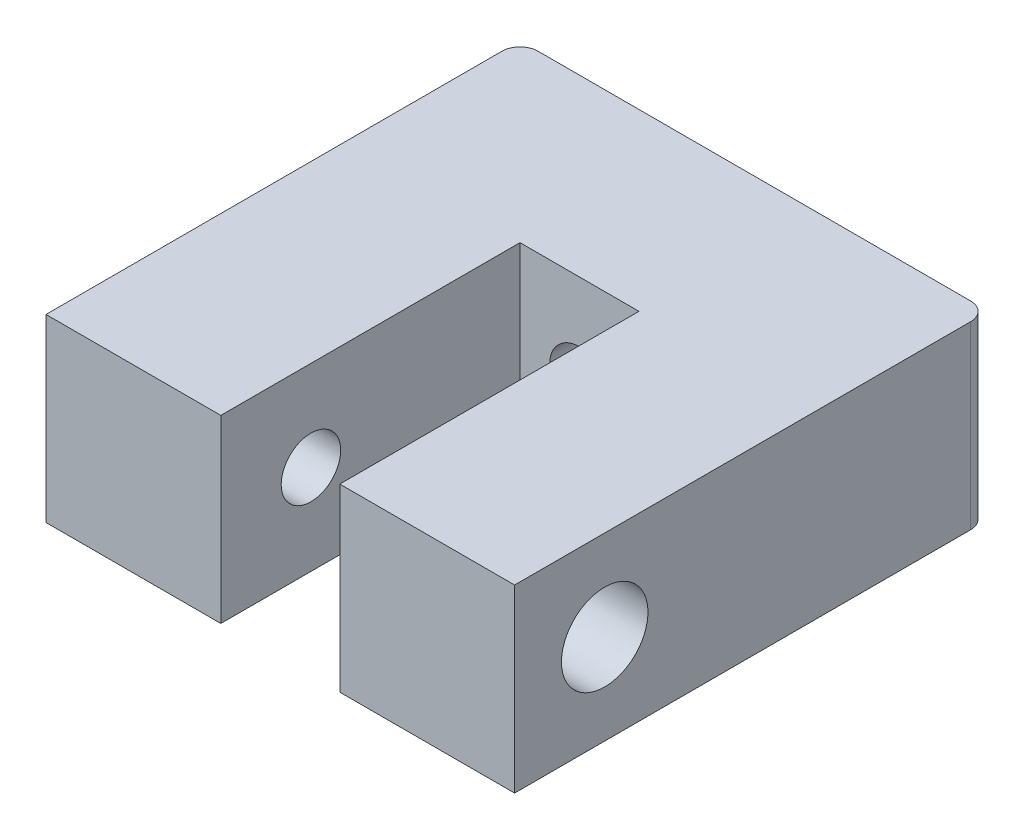
SolidWorks part; units mm, degrees
material "ABS"
ref_plane "Front Plane" through (0, 0, 0) normal (0, 0, 1) x (1, 0, 0)
ref_plane "Top Plane" through (0, 0, 0) normal (0, 1, 0) x (1, 0, 0)
ref_plane "Right Plane" through (0, 0, 0) normal (1, 0, 0) x (0, 0, -1)
sketch "Sketch1" plane through (0, 0, 0) normal (0, 1, 0) x (1, 0, 0)
  line L0 (-3.3, 3.3) -> (-3.3, -13.3)
  line L1 (-3.3, 3.3) -> (3.3, 3.3) construction
  line L2 (-3.3, 3.3) -> (-3.3, -3.3) construction
  line L3 (-3.3, -3.3) -> (3.3, -3.3) construction
  line L4 (3.3, 3.3) -> (3.3, -3.3) construction
  line L5 (-3.3, 3.3) -> (3.3, 3.3)
  line L6 (3.3, 3.3) -> (3.3, -13.3)
  line L7 (3.3, -13.3) -> (13, -13.3)
  line L8 (13, -13.3) -> (13, 13)
  line L9 (13, 13) -> (-13, 13)
  line L10 (-13, 13) -> (-13, -13.3)
  line L11 (-13, -13.3) -> (-3.3, -13.3)
  line L12 (-13, 13) -> (-3.3, 3.3) construction
  point P4 (0, 3.3)
  point P6 (-3.3, 0)
  point P14 (0, 13)
  dimension "D1" = 6.6
  dimension "D2" = 45
  dimension "D3" = 26
  dimension "D4" = 10
extrude "Boss-Extrude1" add sketch "Sketch1" along normal blind 10 contours L9 L10 L11 L0 L5 L6 L7 L8
sketch "Sketch2" plane through (-13, 0, 0) normal (-1, 0, 0) x (0, 0, 1)
  line L0 (-13, 0) -> (13.3, 0) construction
  line L5 (13.3, 10) -> (3.3, 10)
  line L6 (13.3, 10) -> (13.3, 0)
  line L7 (13.3, 0) -> (3.3, 0)
  line L8 (3.3, 10) -> (3.3, 0)
  circle A0 centre (8.3, 5) radius 2 construction
  point P0 (8.3, 10)
  point P10 (0, 0)
  point P11 (3.3, 5)
  dimension "D2" = 4
hole_wizard "Tap Drill for M4x0.7 Tap1" positions "3DSketch1" profile "Sketch3" hole size "M4x0.7" standard "ANSI Metric"
sketch3d "3DSketch1"
  point P0 (-13, 5, 8.3)
  point P3 (-6, 3, 6.2)
sketch "Sketch3" plane through (-13, 5, 8.3) normal (0, 1, 0) x (0, 0, 1)
  line L0 (0, 0) -> (0, 9.7)
  line L1 (0, 9.7) -> (1.65, 9.7)
  line L2 (1.65, 9.7) -> (1.65, 0)
  line L5 (1.65, 0) -> (0, 0)
  line L11 (0, -6.35) -> (0, 107.95) construction
  dimension "Thru Hole Dia." = 3.3
  dimension "Thru Hole Depth" = 9.7
sketch "Sketch4" plane through (3.3, 0, 0) normal (-1, 0, 0) x (0, 0, 1)
  circle A0 centre (8.3, 5) radius 2
  dimension "D1" = 4
hole_wizard "M4 Clearance Hole1" positions "3DSketch2" profile "Sketch5" hole size "M4" standard "ANSI Metric"
sketch3d "3DSketch2"
  point P0 (3.3, 5, 8.3)
  point P3 (3.2, 3, 6.2)
sketch "Sketch5" plane through (3.3, 5, 8.3) normal (0, 1, 0) x (0, 0, 1)
  line L0 (0, 0) -> (0, 9.7)
  line L1 (0, 9.7) -> (2.4, 9.7)
  line L2 (2.4, 9.7) -> (2.4, 0)
  line L5 (2.4, 0) -> (0, 0)
  line L11 (0, -6.35) -> (0, 107.95) construction
  dimension "Thru Hole Dia." = 4.8
  dimension "Thru Hole Depth" = 9.7
sketch "Sketch6" plane through (0, 0, -13) normal (0, 0, -1) x (-1, 0, 0)
  line L1 (-13, 10) -> (13, 10)
  line L2 (-13, 10) -> (-13, 0)
  line L3 (-13, 0) -> (13, 0)
  line L4 (13, 10) -> (13, 0)
  circle A0 centre (0, 5) radius 2 construction
  point P9 (13, 5)
  dimension "D1" = 4
hole_wizard "Tap Drill for M4x0.7 Tap2" positions "3DSketch3" profile "Sketch7" hole size "M4x0.7" standard "ANSI Metric" end condition up to next
sketch3d "3DSketch3"
  point P0 (0, 5, -13)
  point P3 (0, 3, -6)
sketch "Sketch7" plane through (0, 5, -13) normal (1, 0, 0) x (0, 1, 0)
  line L0 (0, 0) -> (0, 9.7)
  line L1 (0, 9.7) -> (1.65, 9.7)
  line L2 (1.65, 9.7) -> (1.65, 0)
  line L5 (1.65, 0) -> (0, 0)
  line L11 (0, -6.35) -> (0, 107.95) construction
  dimension "Thru Hole Dia." = 3.3
  dimension "Thru Hole Depth" = 9.7
fillet "Fillet1" radius 1 2 edges at (13, 5, -13) (-13, 5, -13)
